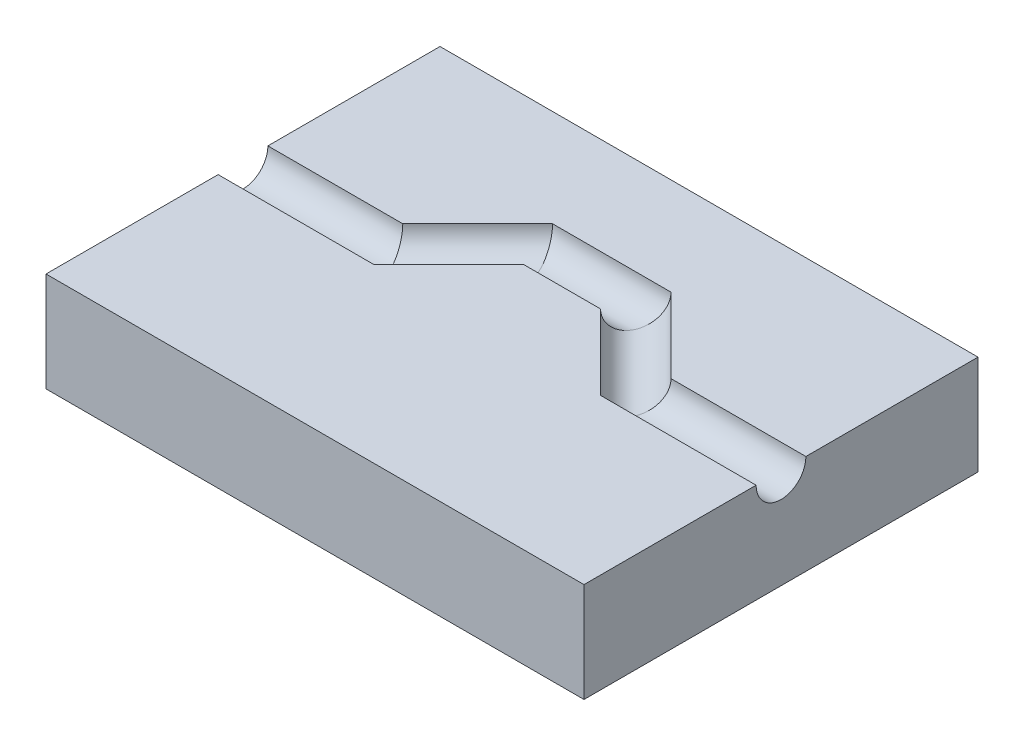
SolidWorks part; units mm, degrees
ref_plane "Front Plane" through (0, 0, 0) normal (0, 0, 1) x (1, 0, 0)
ref_plane "Top Plane" through (0, 0, 0) normal (0, 1, 0) x (1, 0, 0)
ref_plane "Right Plane" through (0, 0, 0) normal (1, 0, 0) x (0, 0, -1)
sketch "Sketch1" plane through (0, 0, 0) normal (0, 1, 0) x (1, 0, 0)
  line L1 (-54.0546, 39.5881) -> (54.0546, 39.5881)
  line L2 (-54.0546, 39.5881) -> (-54.0546, -39.5881)
  line L3 (-54.0546, -39.5881) -> (54.0546, -39.5881)
  line L4 (54.0546, 39.5881) -> (54.0546, -39.5881)
  line L5 (-54.0546, 39.5881) -> (54.0546, -39.5881) construction
  line L6 (-54.0546, -39.5881) -> (54.0546, 39.5881) construction
  point P0 (0, 0)
extrude "Boss-Extrude1" add sketch "Sketch1" along normal blind 20
sketch "Sketch2" plane through (0, 20, 0) normal (0, 1, 0) x (1, 0, 0)
  line L0 (-54.0546, 0) -> (-24.8784, 0)
  line L1 (-54.0546, 39.5881) -> (-54.0546, -39.5881) construction
  line L2 (-24.8784, 0) -> (-9.8302, 15.0482)
  line L3 (-9.8302, 15.0482) -> (9.8302, 15.0482)
  line L5 (24.8784, 0) -> (9.8302, 15.0482)
  line L6 (54.0546, 0) -> (24.8784, 0)
sweep "Cut-Sweep1" cut path "Sketch2" circular profile diameter 10 parameters "D3"=10
